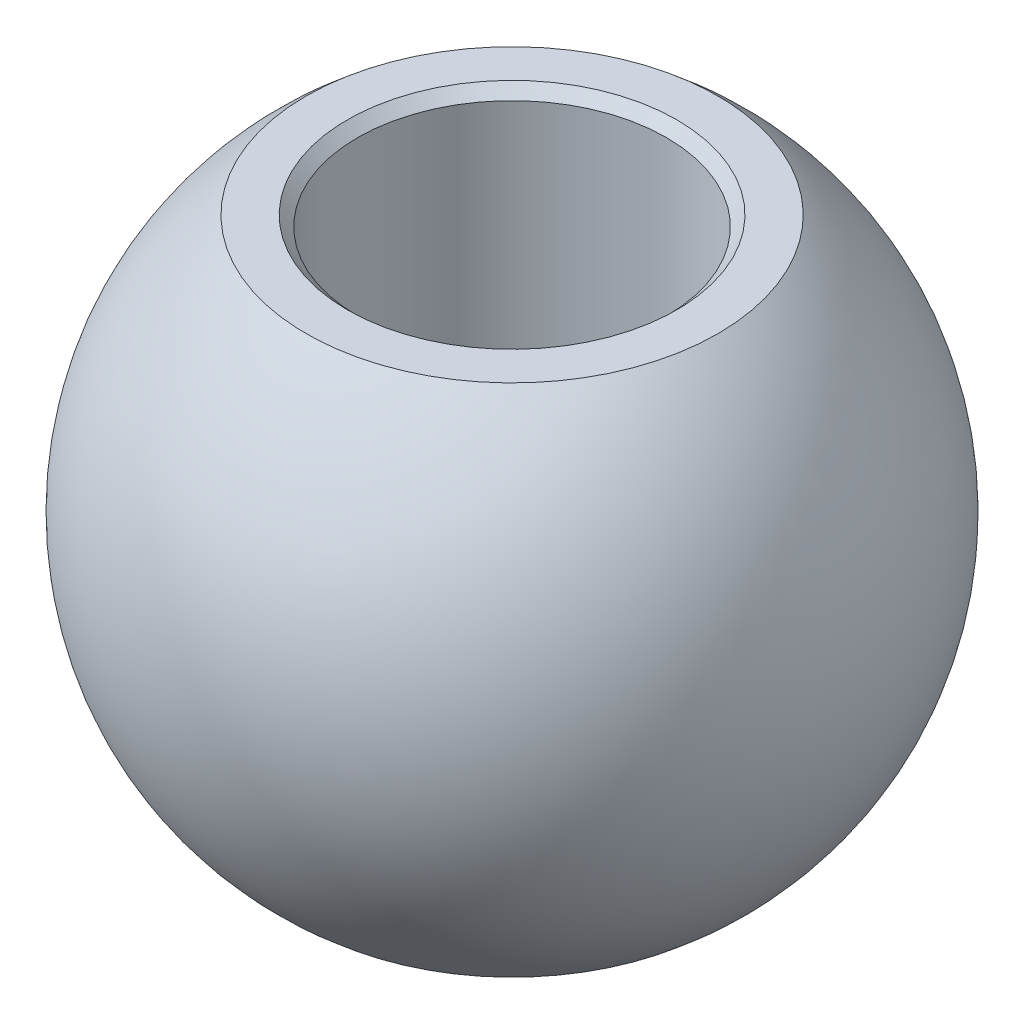
SolidWorks part; units mm, degrees
material "Brass"
ref_plane "Front Plane" through (0, 0, 0) normal (0, 0, 1) x (1, 0, 0)
ref_plane "Top Plane" through (0, 0, 0) normal (0, 1, 0) x (1, 0, 0)
ref_plane "Right Plane" through (0, 0, 0) normal (1, 0, 0) x (0, 0, -1)
sketch "Sketch1" plane through (0, 0, 0) normal (0, 0, 1) x (1, 0, 0)
  line L0 (0, 0) -> (0, -50000) construction
  line L1 (0, 5) -> (2, 5)
  line L2 (0, 0) -> (2, 0)
  line L3 (0, 5) -> (0, 0)
  arc A1 (2, 0) -> (2, 5) centre (0, 2.5) ccw
  dimension "D1" = 2
  dimension "D2" = 5
revolve "Revolve2" add sketch "Sketch1" angle 360 about L0
sketch "Sketch2" plane through (0, 5, 0) normal (0, 1, 0) x (1, 0, 0)
  circle A0 centre (0, 0) radius 1.5
  dimension "D1" = 3
extrude "Cut-Extrude1" cut sketch "Sketch2" against normal through all
chamfer "Chamfer1" distance 0.1 angle 45 2 edges at (0, 5, 1.5) (0, 0, 1.5)
